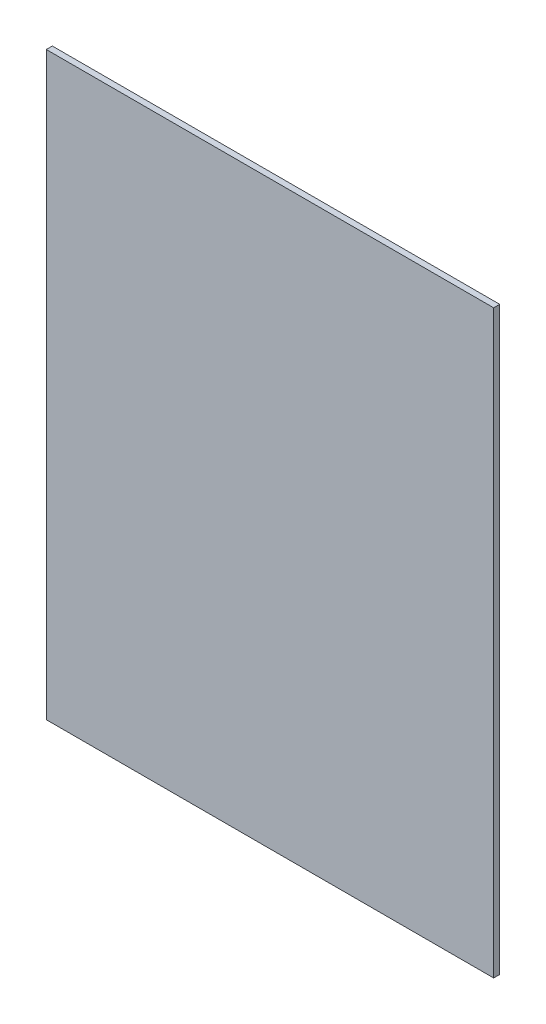
SolidWorks part; units mm, degrees
material "Glass"
ref_plane "Front Plane" through (0, 0, 0) normal (0, 0, 1) x (1, 0, 0)
ref_plane "Top Plane" through (0, 0, 0) normal (0, 1, 0) x (1, 0, 0)
ref_plane "Right Plane" through (0, 0, 0) normal (1, 0, 0) x (0, 0, -1)
sketch "Sketch1" plane through (0, 0, 0) normal (0, 0, 1) x (1, 0, 0)
  line L1 (-117.475, -152.4) -> (117.475, -152.4)
  line L2 (-117.475, -152.4) -> (-117.475, 152.4)
  line L3 (-117.475, 152.4) -> (117.475, 152.4)
  line L4 (117.475, -152.4) -> (117.475, 152.4)
  line L5 (-117.475, -152.4) -> (117.475, 152.4) construction
  line L6 (-117.475, 152.4) -> (117.475, -152.4) construction
  point P0 (0, 0)
  dimension "D1" = 304.8
  dimension "D2" = 234.95
extrude "Boss-Extrude1" add sketch "Sketch1" along normal blind 3.175
